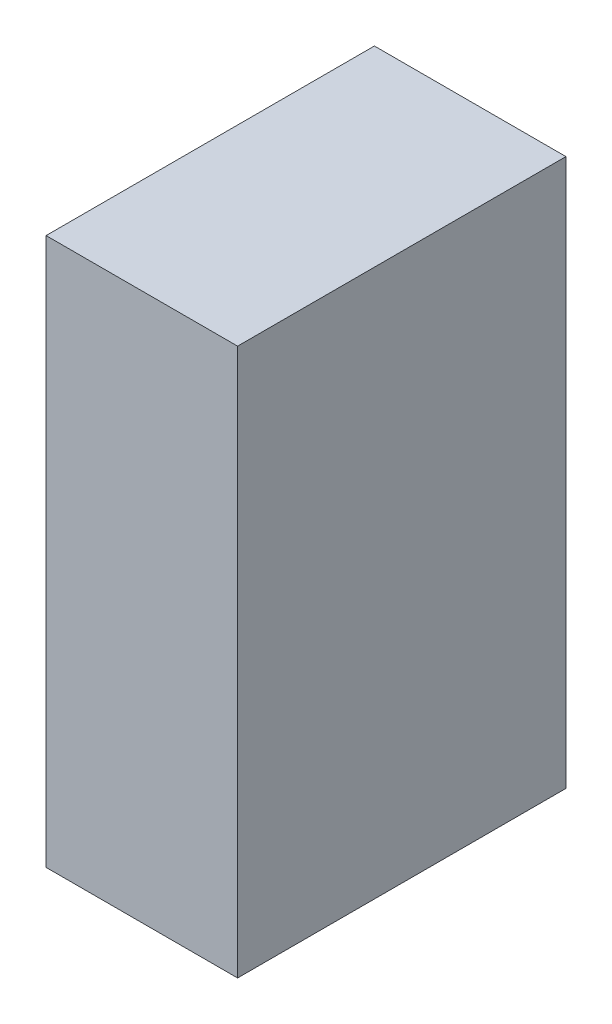
SolidWorks part; units mm, degrees
ref_plane "Front Plane" through (0, 0, 0) normal (0, 0, 1) x (1, 0, 0)
ref_plane "Top Plane" through (0, 0, 0) normal (0, 1, 0) x (1, 0, 0)
ref_plane "Right Plane" through (0, 0, 0) normal (1, 0, 0) x (0, 0, -1)
other "Configuration Table"
sketch "Sketch1" plane through (0, 0, 0) normal (0, 0, 1) x (1, 0, 0)
  line L1 (565, 180) -> (600, 180)
  line L2 (565, 180) -> (565, 280)
  line L3 (565, 280) -> (600, 280)
  line L4 (600, 180) -> (600, 280)
extrude "PACK_pano_servo_surucu_2_1" add sketch "Sketch1" against normal blind 60 from offset 188 separate body
